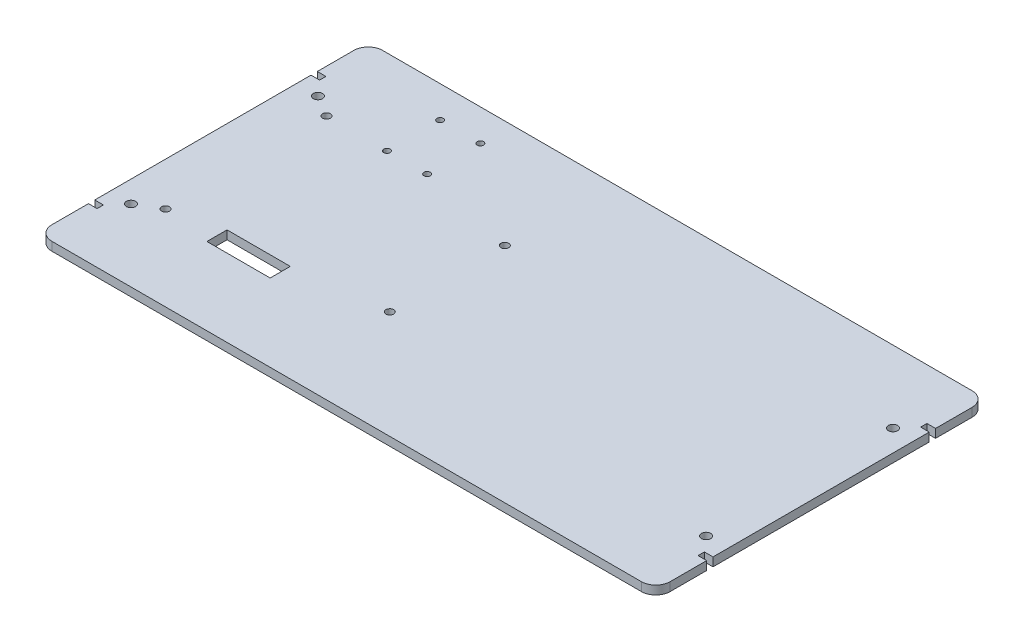
SolidWorks part; units mm, degrees
ref_plane "Front Plane" through (0, 0, 0) normal (0, 0, 1) x (1, 0, 0)
ref_plane "Top Plane" through (0, 0, 0) normal (0, 1, 0) x (1, 0, 0)
ref_plane "Right Plane" through (0, 0, 0) normal (1, 0, 0) x (0, 0, -1)
sketch "Sketch1" plane through (0, 0, 0) normal (0, 1, 0) x (1, 0, 0)
  line L0 (-107.5, 0) -> (107.5, 0) construction
  line L1 (-107.5, -57.5) -> (107.5, -57.5) construction
  line L2 (-107.5, -57.5) -> (-107.5, 57.5) construction
  line L3 (-107.5, 57.5) -> (107.5, 57.5) construction
  line L4 (107.5, -57.5) -> (107.5, 57.5) construction
  line L5 (-107.5, -57.5) -> (107.5, 57.5) construction
  line L6 (-107.5, 57.5) -> (107.5, -57.5) construction
  line L7 (0, 57.5) -> (0, -57.5) construction
  line L8 (-75.5, -23.6) -> (-53.5, -23.6)
  line L9 (-75.5, -23.6) -> (-75.5, -30.6)
  line L10 (-75.5, -30.6) -> (-53.5, -30.6)
  line L11 (-53.5, -23.6) -> (-53.5, -30.6)
  line L12 (-75.5, -23.6) -> (-53.5, -30.6) construction
  line L13 (-75.5, -30.6) -> (-53.5, -23.6) construction
  line L14 (-64.5, -27.1) -> (-64.5, 57.5) construction
  line L22 (-107.5, 57.5) -> (107.5, 57.5)
  line L25 (107.5, -57.5) -> (-107.5, -57.5)
  line L27 (-107.5, 39.8) -> (-104.5, 39.8)
  line L28 (-104.5, 39.8) -> (-104.5, 37.6)
  line L29 (-104.5, 37.6) -> (-107.5, 37.6)
  line L30 (-104.5, -37.6) -> (-107.5, -37.6)
  line L31 (-104.5, -39.8) -> (-104.5, -37.6)
  line L32 (-107.5, -39.8) -> (-104.5, -39.8)
  line L33 (-107.5, 57.5) -> (-107.5, 39.8)
  line L34 (-107.5, 37.6) -> (-107.5, -37.6)
  line L35 (-107.5, -39.8) -> (-107.5, -57.5)
  line L36 (107.5, -39.8) -> (107.5, -57.5)
  line L37 (107.5, -39.8) -> (104.5, -39.8)
  line L38 (104.5, -39.8) -> (104.5, -37.6)
  line L39 (104.5, -37.6) -> (107.5, -37.6)
  line L40 (107.5, 37.6) -> (107.5, -37.6)
  line L41 (104.5, 37.6) -> (107.5, 37.6)
  line L42 (104.5, 39.8) -> (104.5, 37.6)
  line L43 (107.5, 39.8) -> (104.5, 39.8)
  line L44 (107.5, 57.5) -> (107.5, 39.8)
  circle A0 centre (-92.5, 28) radius 1.35
  circle A1 centre (-22.5, 20) radius 1.35
  circle A2 centre (-92.5, -28) radius 1.35
  circle A3 centre (-22.5, -20) radius 1.35
  circle A4 centre (-100, 32.5) radius 1.6
  circle A5 centre (100, 32.5) radius 1.6
  circle A6 centre (100, -32.5) radius 1.6
  circle A7 centre (-100, -32.5) radius 1.6
  circle A21 centre (-71.5, 46.5) radius 1.1
  circle A22 centre (-71.5, 28) radius 1.1
  circle A23 centre (-57.5, 46.5) radius 1.1
  circle A24 centre (-57.5, 28) radius 1.1
  point P0 (0, 0)
  point P16 (-64.5, -27.1)
  dimension "D3" = 2.7
  dimension "D5" = 2.7
  dimension "D13" = 3.2
  dimension "D16" = 2.2
  dimension "D17" = 3
  dimension "D18" = 37.6
  dimension "D24" = 2.2
  dimension "D26" = 2.2
  dimension "D1" = 115
  dimension "D2" = 215
  dimension "D4" = 28
  dimension "D6" = 70
  dimension "D7" = 8
  dimension "D8" = 92.5
  dimension "D9" = 7
  dimension "D10" = 22
  dimension "D11" = 28
  dimension "D12" = 0.9
  dimension "D14" = 7.5
  dimension "D15" = 25
  dimension "D25" = 7
  dimension "D27" = 18.5
extrude "Boss-Extrude1" add sketch "Sketch1" along normal blind 3
fillet "Fillet1" radius 5 4 edges at (107.5, 1.5, 57.5) (107.5, 1.5, -57.5) (-107.5, 1.5, 57.5) (-107.5, 1.5, -57.5)
